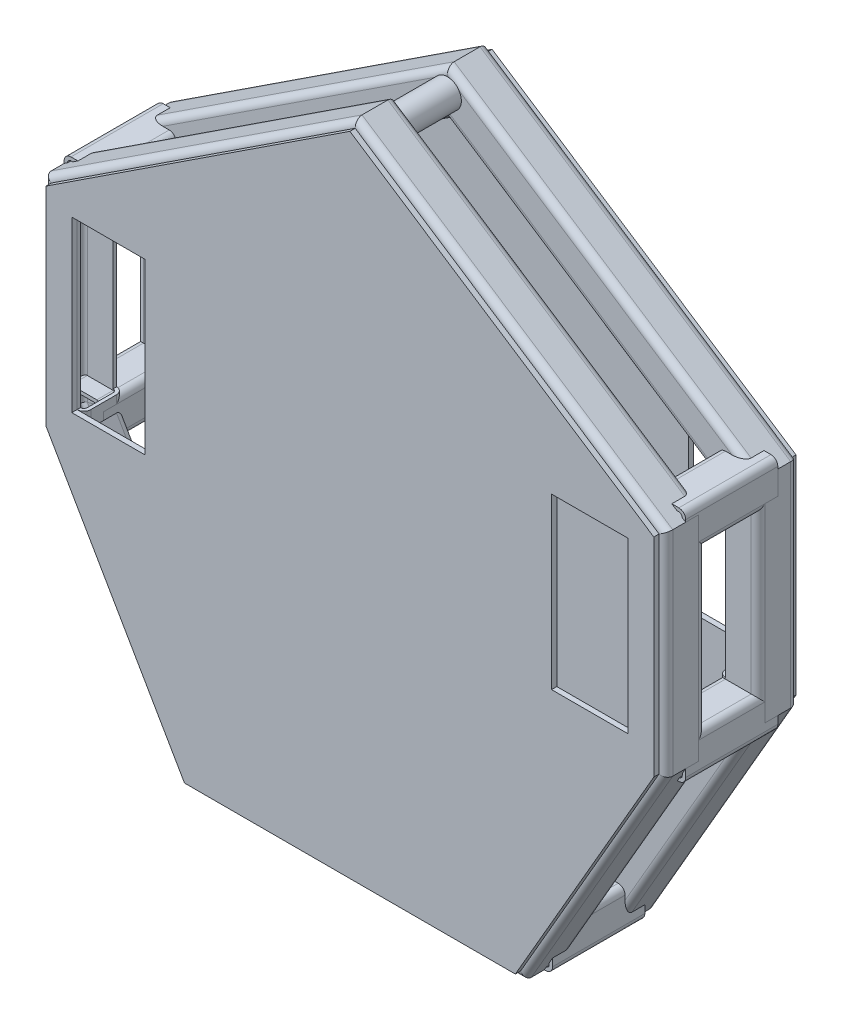
SolidWorks part; units mm, degrees
ref_plane "Front Plane" through (0, 0, 0) normal (0, 0, 1) x (1, 0, 0)
ref_plane "Top Plane" through (0, 0, 0) normal (0, 1, 0) x (1, 0, 0)
ref_plane "Right Plane" through (0, 0, 0) normal (1, 0, 0) x (0, 0, -1)
sketch "Sketch2" plane through (0, 0, 0) normal (0, 0, 1) x (1, 0, 0)
  line L7 (-356.066, 268.7117) -> (-135.0297, 413.7117)
  line L8 (-15.0297, -56.2883) -> (-255.0297, -56.2883)
  line L9 (86.0066, 118.7117) -> (86.0066, 268.7117)
  line L11 (-356.066, 118.7117) -> (-356.066, 268.7117)
  line L12 (-135.0297, 413.7117) -> (86.0066, 268.7117)
  line L13 (86.0066, 268.7117) -> (86.0066, 118.7117)
  line L14 (86.0066, 118.7117) -> (-15.0297, -56.2883)
  line L15 (-356.066, 268.7117) -> (-356.066, 118.7117)
  line L16 (-356.066, 118.7117) -> (-255.0297, -56.2883)
  dimension "D1" = 175
  dimension "D2" = 175
  dimension "D3" = 60
  dimension "D4" = 60
  dimension "D5" = 240
  dimension "D6" = 101.0363
  dimension "D7" = 150
  dimension "D8" = 150
  dimension "D9" = 470
ref_plane "Plane1" through (0, 0, 70) normal (0, 0, 1) x (1, 0, 0)
sketch "Sketch3" plane through (0, 0, 70) normal (0, 0, 1) x (1, 0, 0)
  line L0 (-135.0297, 413.7117) -> (86.0066, 268.7117) construction
  line L1 (86.0066, 118.7117) -> (86.0066, 268.7117) construction
  line L2 (86.0066, 118.7117) -> (-15.0297, -56.2883) construction
  line L3 (-15.0297, -56.2883) -> (-255.0297, -56.2883) construction
  line L4 (-356.066, 118.7117) -> (-255.0297, -56.2883) construction
  line L5 (-356.066, 118.7117) -> (-356.066, 268.7117) construction
  line L6 (-356.066, 268.7117) -> (-135.0297, 413.7117) construction
  line L7 (-135.0297, 413.7117) -> (86.0066, 268.7117)
  line L8 (86.0066, 118.7117) -> (86.0066, 268.7117)
  line L9 (86.0066, 118.7117) -> (-15.0297, -56.2883)
  line L10 (-15.0297, -56.2883) -> (-255.0297, -56.2883)
  line L11 (-356.066, 118.7117) -> (-255.0297, -56.2883)
  line L12 (-356.066, 118.7117) -> (-356.066, 268.7117)
  line L13 (-356.066, 268.7117) -> (-135.0297, 413.7117)
  dimension "D1" = 175
sketch3d "3DSketch1"
  line L0 (-356.066, 268.7117, 70) -> (-356.066, 268.7117, 0)
  line L1 (-356.066, 268.7117, 70) -> (-135.0297, 413.7117, 70) construction
  line L2 (-356.066, 118.7117, 70) -> (-356.066, 268.7117, 70) construction
  line L3 (-356.066, 118.7117, 0) -> (-356.066, 268.7117, 0) construction
  line L6 (86.0066, 118.7117, 0) -> (86.0066, 118.7117, 70)
  line L7 (-15.0297, -56.2883, 70) -> (-15.0297, -56.2883, 0)
  line L8 (-356.066, 118.7117, 70) -> (-356.066, 118.7117, 0)
  line L9 (86.0066, 268.7117, 70) -> (86.0066, 268.7117, 0)
  line L10 (-255.0297, -56.2883, 70) -> (-255.0297, -56.2883, 0)
  line L11 (-135.0297, 413.7117, 0) -> (-135.0297, 413.7117, 70)
other "Square tube 30 X 30 X 2.6(1)"
ref_plane "Plane2" through (-15.0297, -56.2883, 70) normal (-1, 0, 0) x (0, -1, 0)
sketch "Sketch1" plane through (-15.0297, -56.2883, 70) normal (-1, 0, 0) x (0, -1, 0)
  line L0 (-9.8, -12.4) -> (9.8, -12.4)
  line L1 (-12.4, -9.8) -> (-12.4, 9.8)
  line L2 (9.8, 12.4) -> (-9.8, 12.4)
  line L3 (12.4, 9.8) -> (12.4, -9.8)
  line L4 (-9.8, -15) -> (9.8, -15)
  line L5 (-15, -9.8) -> (-15, 9.8)
  line L6 (9.8, 15) -> (-9.8, 15)
  line L7 (15, 9.8) -> (15, -9.8)
  arc A0 (15, 9.8) -> (9.8, 15) centre (9.8, 9.8) ccw
  arc A1 (9.8, -15) -> (15, -9.8) centre (9.8, -9.8) ccw
  arc A2 (-15, -9.8) -> (-9.8, -15) centre (-9.8, -9.8) ccw
  arc A3 (-9.8, 15) -> (-15, 9.8) centre (-9.8, 9.8) ccw
  arc A4 (-9.8, 12.4) -> (-12.4, 9.8) centre (-9.8, 9.8) ccw
  arc A5 (12.4, 9.8) -> (9.8, 12.4) centre (9.8, 9.8) ccw
  arc A6 (9.8, -12.4) -> (12.4, -9.8) centre (9.8, -9.8) ccw
  arc A7 (-12.4, -9.8) -> (-9.8, -12.4) centre (-9.8, -9.8) ccw
  point P0 (-15, 0)
  point P1 (15, 0)
  point P2 (0, 15)
  point P3 (0, -15)
  point P4 (0, 0)
  point P5 (-15, -15)
  point P6 (15, -15)
  point P7 (15, 15)
  point P8 (-15, 15)
  point P33 (0, 0)
  dimension "D1" = 5.2
  dimension "Thickness" = 2.6
  dimension "V_leg" = 30
other "Square tube 30 X 30 X 2.6(2)"
ref_plane "Plane3" through (-15.0297, -56.2883, 0) normal (-1, 0, 0) x (0, -1, 0)
sketch "Sketch11" plane through (-15.0297, -56.2883, 0) normal (-1, 0, 0) x (0, -1, 0)
  line L0 (-9.8, -12.4) -> (9.8, -12.4)
  line L1 (-12.4, -9.8) -> (-12.4, 9.8)
  line L2 (9.8, 12.4) -> (-9.8, 12.4)
  line L3 (12.4, 9.8) -> (12.4, -9.8)
  line L4 (-9.8, -15) -> (9.8, -15)
  line L5 (-15, -9.8) -> (-15, 9.8)
  line L6 (9.8, 15) -> (-9.8, 15)
  line L7 (15, 9.8) -> (15, -9.8)
  arc A0 (15, 9.8) -> (9.8, 15) centre (9.8, 9.8) ccw
  arc A1 (9.8, -15) -> (15, -9.8) centre (9.8, -9.8) ccw
  arc A2 (-15, -9.8) -> (-9.8, -15) centre (-9.8, -9.8) ccw
  arc A3 (-9.8, 15) -> (-15, 9.8) centre (-9.8, 9.8) ccw
  arc A4 (-9.8, 12.4) -> (-12.4, 9.8) centre (-9.8, 9.8) ccw
  arc A5 (12.4, 9.8) -> (9.8, 12.4) centre (9.8, 9.8) ccw
  arc A6 (9.8, -12.4) -> (12.4, -9.8) centre (9.8, -9.8) ccw
  arc A7 (-12.4, -9.8) -> (-9.8, -12.4) centre (-9.8, -9.8) ccw
  point P0 (-15, 0)
  point P1 (15, 0)
  point P2 (0, 15)
  point P3 (0, -15)
  point P4 (0, 0)
  point P5 (-15, -15)
  point P6 (15, -15)
  point P7 (15, 15)
  point P8 (-15, 15)
  point P33 (0, 0)
  dimension "D1" = 5.2
  dimension "Thickness" = 2.6
  dimension "V_leg" = 30
other "Square tube 30 X 30 X 2.6(3)"
ref_plane "Plane4" through (-356.066, 118.7117, 70) normal (0, 0, -1) x (1, 0, 0)
sketch "Sketch12" plane through (-356.066, 118.7117, 70) normal (0, 0, -1) x (1, 0, 0)
  line L0 (-9.8, -12.4) -> (9.8, -12.4)
  line L1 (-12.4, -9.8) -> (-12.4, 9.8)
  line L2 (9.8, 12.4) -> (-9.8, 12.4)
  line L3 (12.4, 9.8) -> (12.4, -9.8)
  line L4 (-9.8, -15) -> (9.8, -15)
  line L5 (-15, -9.8) -> (-15, 9.8)
  line L6 (9.8, 15) -> (-9.8, 15)
  line L7 (15, 9.8) -> (15, -9.8)
  arc A0 (15, 9.8) -> (9.8, 15) centre (9.8, 9.8) ccw
  arc A1 (9.8, -15) -> (15, -9.8) centre (9.8, -9.8) ccw
  arc A2 (-15, -9.8) -> (-9.8, -15) centre (-9.8, -9.8) ccw
  arc A3 (-9.8, 15) -> (-15, 9.8) centre (-9.8, 9.8) ccw
  arc A4 (-9.8, 12.4) -> (-12.4, 9.8) centre (-9.8, 9.8) ccw
  arc A5 (12.4, 9.8) -> (9.8, 12.4) centre (9.8, 9.8) ccw
  arc A6 (9.8, -12.4) -> (12.4, -9.8) centre (9.8, -9.8) ccw
  arc A7 (-12.4, -9.8) -> (-9.8, -12.4) centre (-9.8, -9.8) ccw
  point P0 (-15, 0)
  point P1 (15, 0)
  point P2 (0, 15)
  point P3 (0, -15)
  point P4 (0, 0)
  point P5 (-15, -15)
  point P6 (15, -15)
  point P7 (15, 15)
  point P8 (-15, 15)
  point P33 (0, 0)
  dimension "D1" = 5.2
  dimension "Thickness" = 2.6
  dimension "V_leg" = 30
sketch "Sketch14" plane through (0, 0, -15) normal (0, 0, -1) x (-1, 0, 0)
  line L0 (135.0297, 425.4322) -> (365.866, 274.0034) construction
  line L1 (365.866, 274.0034) -> (365.866, 116.0858) construction
  line L2 (365.866, 116.0858) -> (260.6878, -66.0883) construction
  line L3 (260.6878, -66.0883) -> (9.3717, -66.0883) construction
  line L4 (9.3717, -66.0883) -> (-95.8066, 116.0858) construction
  line L5 (-95.8066, 116.0858) -> (-95.8066, 274.0034) construction
  line L6 (-95.8066, 274.0034) -> (135.0297, 425.4322) construction
  line L7 (135.0297, 425.4322) -> (365.866, 274.0034)
  line L8 (365.866, 274.0034) -> (365.866, 116.0858)
  line L9 (365.866, 116.0858) -> (260.6878, -66.0883)
  line L10 (260.6878, -66.0883) -> (9.3717, -66.0883)
  line L11 (9.3717, -66.0883) -> (-95.8066, 116.0858)
  line L12 (-95.8066, 116.0858) -> (-95.8066, 274.0034)
  line L13 (-95.8066, 274.0034) -> (135.0297, 425.4322)
extrude "Boss-Extrude1" add sketch "Sketch14" along normal blind 4 separate body
sketch "Sketch15" plane through (0, 0, 85) normal (0, 0, 1) x (1, 0, 0)
  line L0 (95.8066, 274.0034) -> (-135.0297, 425.4322) construction
  line L1 (95.8066, 116.0858) -> (95.8066, 274.0034) construction
  line L2 (-9.3717, -66.0883) -> (95.8066, 116.0858) construction
  line L3 (-260.6878, -66.0883) -> (-9.3717, -66.0883) construction
  line L4 (-365.866, 116.0858) -> (-260.6878, -66.0883) construction
  line L5 (-365.866, 274.0034) -> (-365.866, 116.0858) construction
  line L6 (-135.0297, 425.4322) -> (-365.866, 274.0034) construction
  line L7 (95.8066, 274.0034) -> (-135.0297, 425.4322)
  line L8 (95.8066, 116.0858) -> (95.8066, 274.0034)
  line L9 (-9.3717, -66.0883) -> (95.8066, 116.0858)
  line L10 (-260.6878, -66.0883) -> (-9.3717, -66.0883)
  line L11 (-365.866, 116.0858) -> (-260.6878, -66.0883)
  line L12 (-365.866, 274.0034) -> (-365.866, 116.0858)
  line L13 (-135.0297, 425.4322) -> (-365.866, 274.0034)
extrude "Boss-Extrude2" add sketch "Sketch15" along normal blind 4 separate body
other "Pipe 21.3 X 2.3(4)"
ref_plane "Plane5" through (-135.0297, 413.7117, 0) normal (0, 0, 1) x (1, 0, 0)
sketch "Sketch17" plane through (-135.0297, 413.7117, 0) normal (0, 0, 1) x (1, 0, 0)
  circle A0 centre (0, 0) radius 8.35
  circle A1 centre (0, 0) radius 10.65
  point P3 (0, 10.65)
  point P5 (-10.65, 0)
  point P6 (0, -10.65)
  point P7 (10.65, 0)
  point P8 (0, 0)
  dimension "In_dia" = 16.7
  dimension "Out_dia" = 21.3
sketch "Sketch18" plane through (0, 0, 89) normal (0, 0, 1) x (1, 0, 0)
  line L0 (-346.266, 263.4201) -> (-346.266, 121.3376) construction
  line L1 (-346.266, 263.4201) -> (-290.6251, 263.4201)
  line L2 (-346.266, 263.4201) -> (-346.266, 134.784)
  line L3 (-346.266, 134.784) -> (-290.6251, 134.784)
  line L4 (-290.6251, 263.4201) -> (-290.6251, 134.784)
  line L5 (76.2066, 121.3376) -> (76.2066, 263.4201) construction
  line L6 (76.2066, 263.4201) -> (18.1345, 263.4201)
  line L7 (76.2066, 263.4201) -> (76.2066, 134.784)
  line L8 (76.2066, 134.784) -> (18.1345, 134.784)
  line L9 (18.1345, 263.4201) -> (18.1345, 134.784)
extrude "Cut-Extrude1" cut sketch "Sketch18" against normal through all both and the other way through all
